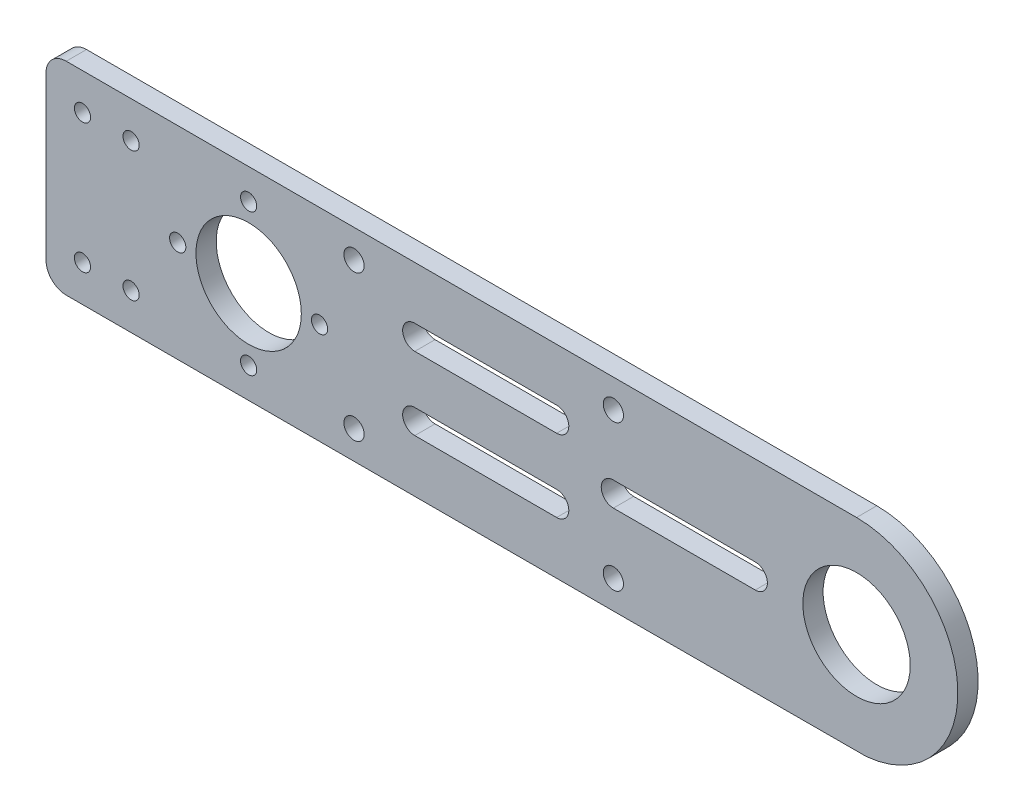
SolidWorks part; units mm, degrees
other "标注1"
sketch "草图2"
material "6061 合金"
ref_plane "前视基准面" through (0, 0, 0) normal (0, 0, 1) x (1, 0, 0)
ref_plane "上视基准面" through (0, 0, 0) normal (0, 1, 0) x (1, 0, 0)
ref_plane "右视基准面" through (0, 0, 0) normal (1, 0, 0) x (0, 0, -1)
sketch "草图1" plane through (0, 0, 0) normal (0, 0, 1) x (1, 0, 0)
  line L1 (0, 0) -> (184, 0) construction
  line L3 (0, 10.0957) -> (35, 10.0957) construction
  line L4 (0, 25) -> (124.8693, 25)
  line L17 (0, -25) -> (124.8693, -25)
  line L21 (0, 0) -> (5, 0) construction
  line L22 (5, 0) -> (5, 16) construction
  line L23 (124.8693, 25) -> (184, 25)
  line L24 (124.8693, -25) -> (186.4905, -24.8756)
  line L53 (75, -9) -> (110, -9) construction
  line L56 (75, -12) -> (110, -12)
  line L72 (130.7557, 4.1147) -> (130.7557, 16.1147) construction
  line L73 (130.7557, 16.1147) -> (160.7557, 16.1147) construction
  line L74 (160.7557, 16.1147) -> (130.7557, 4.1147) construction
  line L78 (130.7557, 4.1147) -> (158.292, 4.1147) construction
  line L79 (144.7181, 4.1147) -> (160.7557, 10.5297) construction
  line L80 (144.7181, 4.1147) -> (160.7557, 4.1147) construction
  line L81 (160.7557, 4.1147) -> (160.7557, 10.5297) construction
  line L91 (130.7557, 17.1147) -> (160.7557, 17.1147) construction
  line L92 (129.7557, 16.1147) -> (129.7557, 4.1147) construction
  line L93 (131.1271, 3.1862) -> (161.1271, 15.1862) construction
  line L94 (144.4708, -5.0836) -> (160.5084, -11.4986) construction
  line L95 (144.7181, 3.1147) -> (160.7557, 3.1147) construction
  line L96 (161.7557, 10.5297) -> (161.7557, 4.1147) construction
  line L97 (144.4708, 5.0836) -> (160.5084, 11.4986) construction
  line L98 (161.7557, -10.5297) -> (161.7557, -4.1147) construction
  line L99 (144.7181, -3.1147) -> (160.7557, -3.1147) construction
  line L100 (130.7557, -17.1147) -> (160.7557, -17.1147) construction
  line L101 (131.1271, -3.1862) -> (161.1271, -15.1862) construction
  line L102 (129.7557, -16.1147) -> (129.7557, -4.1147) construction
  line L104 (0, 25) -> (-16, 25)
  line L107 (124, 0) -> (159, 0) construction
  line L108 (124, 3) -> (159, 3)
  line L109 (124, -3) -> (159, -3)
  line L110 (-16, 25) -> (-16, -25)
  line L111 (-16, -25) -> (0, -25)
  line L112 (5, 16) -> (-7, 16) construction
  line L113 (75, 9) -> (110, 9) construction
  line L114 (75, 12) -> (110, 12)
  line L115 (75, 6) -> (110, 6)
  line L116 (75, -6) -> (110, -6)
  circle A5 centre (184, 0) radius 13.25
  circle A6 centre (184, 0) radius 16 construction
  arc A7 (186.4905, -24.8756) -> (184, 25) centre (184, 0) ccw
  circle A15 centre (5, 16) radius 2
  circle A16 centre (5, -16) radius 2
  circle A35 centre (60, 18) radius 2.5
  circle A36 centre (124, 18) radius 2.5
  circle A39 centre (34, 0) radius 13
  circle A40 centre (34, 0) radius 17.5 construction
  circle A41 centre (34, 17.5) radius 2
  circle A45 centre (124, -18) radius 2.5
  circle A46 centre (60, -18) radius 2.5
  arc A80 (130.7557, 17.1147) -> (129.7557, 16.1147) centre (130.7557, 16.1147) ccw construction
  arc A81 (129.7557, 4.1147) -> (131.1271, 3.1862) centre (130.7557, 4.1147) ccw construction
  arc A82 (161.1271, 15.1862) -> (160.7557, 17.1147) centre (160.7557, 16.1147) ccw construction
  arc A83 (161.7557, 10.5297) -> (160.5084, 11.4986) centre (160.7557, 10.5297) ccw construction
  arc A84 (160.7557, 3.1147) -> (161.7557, 4.1147) centre (160.7557, 4.1147) ccw construction
  arc A85 (144.4708, 5.0836) -> (144.7181, 3.1147) centre (144.7181, 4.1147) ccw construction
  arc A86 (144.4708, -5.0836) -> (144.7181, -3.1147) centre (144.7181, -4.1147) cw construction
  arc A87 (161.7557, -10.5297) -> (160.5084, -11.4986) centre (160.7557, -10.5297) cw construction
  arc A88 (160.7557, -3.1147) -> (161.7557, -4.1147) centre (160.7557, -4.1147) cw construction
  arc A89 (130.7557, -17.1147) -> (129.7557, -16.1147) centre (130.7557, -16.1147) cw construction
  arc A90 (161.1271, -15.1862) -> (160.7557, -17.1147) centre (160.7557, -16.1147) cw construction
  arc A91 (129.7557, -4.1147) -> (131.1271, -3.1862) centre (130.7557, -4.1147) cw construction
  circle A92 centre (184, 16) radius 1.5 construction
  circle A93 centre (200, 0) radius 1.5 construction
  circle A94 centre (184, -16) radius 1.5 construction
  circle A95 centre (168, 0) radius 1.5 construction
  arc A100 (124, 3) -> (124, -3) centre (124, 0) ccw
  arc A101 (159, -3) -> (159, 3) centre (159, 0) ccw
  circle A102 centre (51.5, 0) radius 2
  circle A103 centre (34, -17.5) radius 2
  circle A104 centre (16.5, 0) radius 2
  circle A105 centre (-7, 16) radius 2
  circle A106 centre (-7, -16) radius 2
  arc A107 (75, 12) -> (75, 6) centre (75, 9) ccw
  arc A108 (110, 6) -> (110, 12) centre (110, 9) ccw
  arc A109 (75, -12) -> (75, -6) centre (75, -9) cw
  arc A110 (110, -6) -> (110, -12) centre (110, -9) cw
  point P29 (92.5, -9)
  point P51 (141.5, 0)
  point P58 (34, 0)
  point P63 (92.5, 9)
  point P147 (184, 0)
  dimension "D7" = 25
  dimension "D8" = 200
  dimension "D12" = 4
  dimension "D13" = 16
  dimension "D14" = 50
  dimension "D19" = 2
  dimension "D23" = 2
  dimension "D27" = 25
  dimension "D28" = 2
  dimension "D29" = 2
  dimension "D30" = 2
  dimension "D31" = 2
  dimension "D32" = 4
  dimension "D2" = 25
  dimension "D4" = 50
  dimension "D5" = 18
  dimension "D6" = 16
  dimension "D20" = 18
  dimension "D21" = 60
  dimension "D25" = 12
  dimension "D26" = 30
  dimension "D33" = 150
extrude "凸台-拉伸1" add sketch "草图1" along normal blind 5
fillet "圆角1" radius 5 2 edges at (-16, -25, 2.5) (-16, 25, 2.5)
